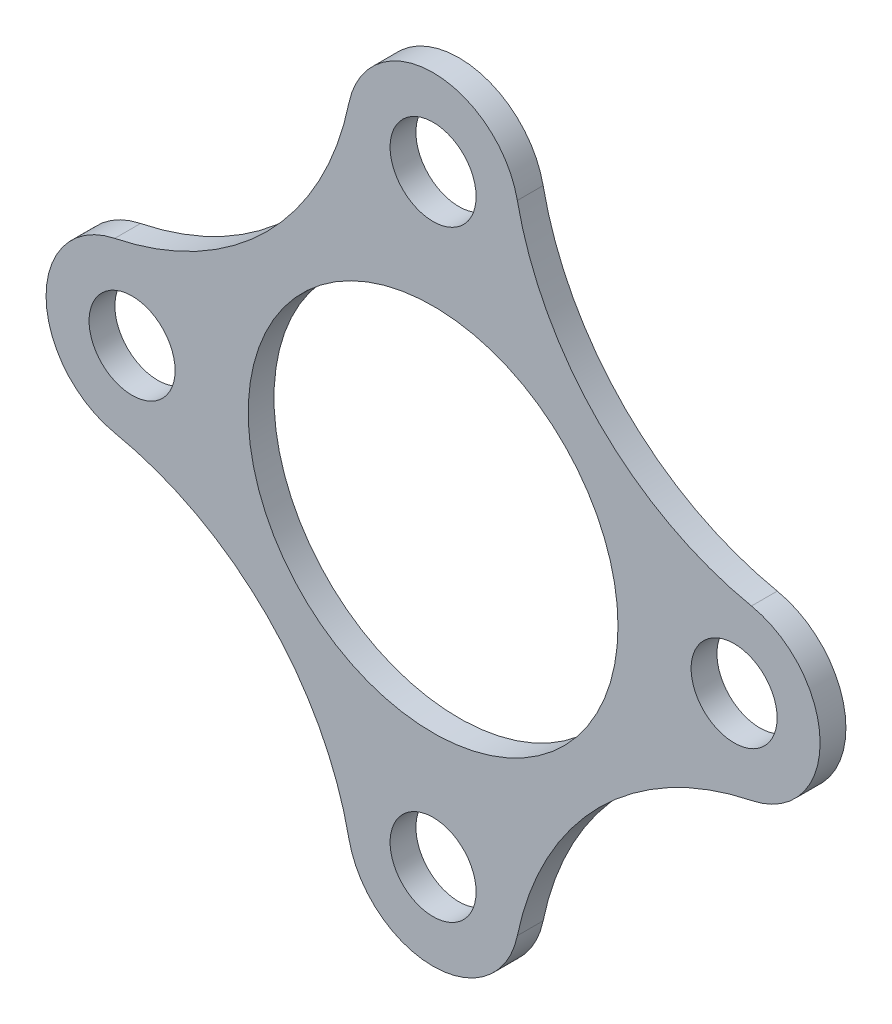
SolidWorks part; units mm, degrees
ref_plane "Płaszczyzna przednia" through (0, 0, 0) normal (0, 0, 1) x (1, 0, 0)
ref_plane "Płaszczyzna górna" through (0, 0, 0) normal (0, 1, 0) x (1, 0, 0)
ref_plane "Płaszczyzna prawa" through (0, 0, 0) normal (1, 0, 0) x (0, 0, -1)
sketch "Szkic1" plane through (0, 0, 0) normal (0, 0, 1) x (1, 0, 0)
  arc A1 (21.5, 0) -> (-21.5, 0) centre (0, 0) ccw
  circle A3 centre (0, 35) radius 5
  arc A4 (10, 35) -> (-10, 35) centre (0, 35) ccw
  circle A7 centre (0, 0) radius 21.5
  arc A8 (35, -10) -> (35, 10) centre (35, 0) ccw
  circle A9 centre (35, 0) radius 5
  arc A10 (-10, -35) -> (10, -35) centre (0, -35) ccw
  circle A11 centre (0, -35) radius 5
  arc A12 (-35, 10) -> (-35, -10) centre (-35, 0) ccw
  circle A13 centre (-35, 0) radius 5
  arc A14 (-10, -35) -> (-35, -10) centre (-35, -35) ccw
  arc A15 (10, -35) -> (35, -10) centre (35, -35) cw
  arc A16 (35, 10) -> (10, 35) centre (35, 35) cw
  arc A17 (-35, 10) -> (-10, 35) centre (-35, 35) ccw
  dimension "D1" = 43
  dimension "D2" = 35
  dimension "D3" = 20
  dimension "D4" = 10
  dimension "D5" = 4
extrude "Dodanie-wyciągnięcie1" add sketch "Szkic1" along normal blind 3
sketch "Szkic2" plane through (0, 0, 0) normal (0, 0, 1) x (1, 0, 0)
  line L4 (37.0167, -9.7945) -> (25.0125, -7.2377)
  line L5 (25.0125, -7.2377) -> (6.5278, -26.0865)
  line L6 (6.5278, -26.0865) -> (9.7945, -37.0167)
  line L7 (-9.7945, -37.0167) -> (-6.1039, -26.0865)
  line L8 (-6.1039, -26.0865) -> (-27.7279, -4.8802)
  line L9 (-27.7279, -4.8802) -> (-37.0167, -9.7945)
  line L10 (-37.0167, 9.7945) -> (-28.7756, 5.7222)
  line L11 (-28.7756, 5.7222) -> (-5.4688, 25.9791)
  line L12 (-5.4688, 25.9791) -> (-9.7945, 37.0167)
  line L13 (9.7945, 37.0167) -> (8.1612, 24.7853)
  line L14 (8.1612, 24.7853) -> (27.5997, 5.7222)
  line L15 (27.5997, 5.7222) -> (37.0167, 9.7945)
  arc A0 (-9.7945, -37.0167) -> (-37.0167, -9.7945) centre (-44.0754, -44.0754) ccw
  arc A1 (-10, -35) -> (10, -35) centre (0, -35) ccw construction
  arc A2 (-35, 10) -> (-35, -10) centre (-35, 0) ccw construction
  arc A3 (9.7945, -37.0167) -> (37.0167, -9.7945) centre (44.0754, -44.0754) cw
  arc A4 (35, -10) -> (35, 10) centre (35, 0) ccw construction
  arc A5 (37.0167, 9.7945) -> (9.7945, 37.0167) centre (44.0754, 44.0754) cw
  arc A6 (10, 35) -> (-10, 35) centre (0, 35) ccw construction
  arc A7 (-9.7945, 37.0167) -> (-37.0167, 9.7945) centre (-44.0754, 44.0754) cw
  dimension "D1" = 35
extrude "Dodanie-wyciągnięcie2" add sketch "Szkic2" along normal up to surface (3 mm away) contours L15 A5 L13 L14 | L12 A7 L10 L11 | A0 L7 L8 L9 | A3 L4 L5 L6 up to face at (0, 0, 3)
